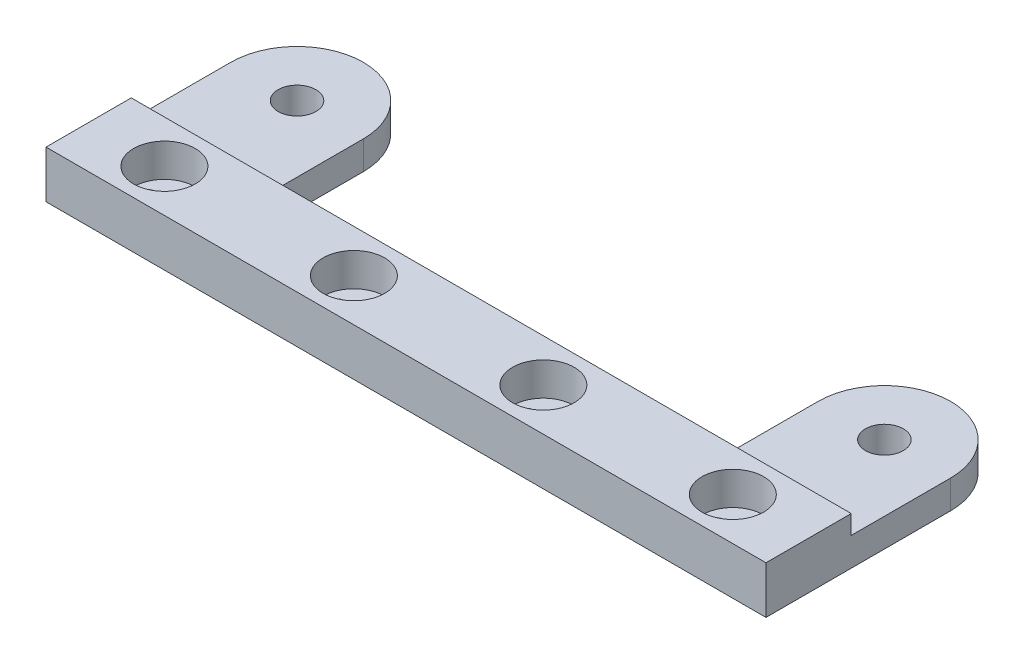
SolidWorks part; units mm, degrees
ref_plane "Front Plane" through (0, 0, 0) normal (0, 0, 1) x (1, 0, 0)
ref_plane "Top Plane" through (0, 0, 0) normal (0, 1, 0) x (1, 0, 0)
ref_plane "Right Plane" through (0, 0, 0) normal (1, 0, 0) x (0, 0, -1)
sketch "Sketch1" plane through (0, 0, 0) normal (0, 1, 0) x (1, 0, 0)
  line L0 (62, 19.5) -> (62, 9)
  line L1 (0, 0) -> (76, 0)
  line L2 (0, 0) -> (0, 9)
  line L3 (0, 9) -> (76, 9)
  line L4 (76, 0) -> (76, 9)
  line L5 (14, 19.5) -> (14, 9)
  line L6 (0, 19.5) -> (0, 9)
  line L7 (76, 9) -> (76, 19.5)
  circle A0 centre (7, 19.5) radius 2
  circle A1 centre (69, 19.5) radius 2
  circle A2 centre (69, 19.5) radius 7
  circle A3 centre (7, 19.5) radius 7
  point P16 (80, 23)
  dimension "D3" = 4
  dimension "D4" = 5
  dimension "D7" = 5
  dimension "D10" = 4
  dimension "D1" = 76
  dimension "D2" = 9
  dimension "D5" = 7
  dimension "D6" = 10.5
  dimension "D8" = 7
  dimension "D9" = 10.5
extrude "Boss-Extrude1" add sketch "Sketch1" along normal blind 3 contours A2 A1 | A2 L3 L7 | A2 L0 L3 | L1 L4 L3 L2 | A3 L3 L5 | A3 A0 | A3 L6 L3
sketch "Sketch2" plane through (0, 3, 0) normal (0, 1, 0) x (1, 0, 0)
  line L0 (76, 0) -> (76, 19.5) construction
  line L1 (0, 0) -> (76, 0)
  line L2 (0, 0) -> (0, 9)
  line L3 (0, 9) -> (76, 9)
  line L4 (76, 0) -> (76, 9)
  dimension "D1" = 9
extrude "Boss-Extrude2" add sketch "Sketch2" along normal blind 2
sketch "Sketch3" plane through (0, 5, 0) normal (0, 1, 0) x (1, 0, 0)
  line L0 (14, 9) -> (0, 9) construction
  line L1 (0, 9) -> (0, 0) construction
  circle A0 centre (8, 4.5) radius 3.25
  circle A1 centre (28, 4.5) radius 3.25
  circle A2 centre (48, 4.5) radius 3.25
  circle A3 centre (68, 4.5) radius 3.25
  circle A8 centre (88, 4.5) radius 3.25 [skipped]
  circle A9 centre (108, 4.5) radius 3.25 [skipped]
  circle A10 centre (128, 4.5) radius 3.25 [skipped]
  circle A11 centre (148, 4.5) radius 3.25 [skipped]
  dimension "D1" = 6.5
  dimension "D2" = 4.5
  dimension "D3" = 8
  dimension "D4" = 8
extrude "Cut-Extrude1" cut sketch "Sketch3" against normal offset from surface (3.5 mm away) 1.5 up to face at (38, 0, -13.75)
sketch "Sketch4" plane through (0, 1.5, 0) normal (0, 1, 0) x (1, 0, 0)
  line L0 (4.75, 4.5) -> (11.25, 4.5) construction
  line L1 (6.25, 4.5) -> (9.75, 4.5) construction
  line L2 (6.25, 5.2) -> (9.75, 5.2)
  line L3 (6.25, 3.8) -> (9.75, 3.8)
  line L4 (26.25, 4.5) -> (29.75, 4.5) construction
  line L5 (26.25, 5.2) -> (29.75, 5.2)
  line L6 (26.25, 3.8) -> (29.75, 3.8)
  line L7 (46.25, 4.5) -> (49.75, 4.5) construction
  line L8 (46.25, 5.2) -> (49.75, 5.2)
  line L9 (46.25, 3.8) -> (49.75, 3.8)
  line L10 (66.25, 4.5) -> (69.75, 4.5) construction
  line L11 (66.25, 5.2) -> (69.75, 5.2)
  line L12 (66.25, 3.8) -> (69.75, 3.8)
  line L178 (106.25, 4.5) -> (109.75, 4.5) construction
  line L179 (106.25, 5.2) -> (109.75, 5.2)
  line L180 (106.25, 3.8) -> (109.75, 3.8)
  line L181 (126.25, 4.5) -> (129.75, 4.5) construction
  line L182 (126.25, 5.2) -> (129.75, 5.2)
  line L183 (126.25, 3.8) -> (129.75, 3.8)
  line L184 (146.25, 4.5) -> (149.75, 4.5) construction
  line L185 (146.25, 5.2) -> (149.75, 5.2)
  line L186 (146.25, 3.8) -> (149.75, 3.8)
  line L187 (86.25, 4.5) -> (89.75, 4.5) construction
  line L188 (86.25, 5.2) -> (89.75, 5.2)
  line L189 (86.25, 3.8) -> (89.75, 3.8)
  line L190 (106.25, 4.5) -> (109.75, 4.5) construction
  line L191 (106.25, 5.2) -> (109.75, 5.2)
  line L192 (106.25, 3.8) -> (109.75, 3.8)
  line L193 (126.25, 4.5) -> (129.75, 4.5) construction
  line L194 (126.25, 5.2) -> (129.75, 5.2)
  line L195 (126.25, 3.8) -> (129.75, 3.8)
  line L196 (146.25, 4.5) -> (149.75, 4.5) construction
  line L197 (146.25, 5.2) -> (149.75, 5.2)
  line L198 (146.25, 3.8) -> (149.75, 3.8)
  line L199 (86.25, 4.5) -> (89.75, 4.5) construction
  line L200 (86.25, 5.2) -> (89.75, 5.2)
  line L201 (86.25, 3.8) -> (89.75, 3.8)
  circle A0 centre (8, 4.5) radius 3.25 construction
  circle A1 centre (8, 4.5) radius 3.25 construction
  arc A2 (6.25, 5.2) -> (6.25, 3.8) centre (6.25, 4.5) ccw
  arc A3 (9.75, 3.8) -> (9.75, 5.2) centre (9.75, 4.5) ccw
  arc A4 (26.25, 5.2) -> (26.25, 3.8) centre (26.25, 4.5) ccw
  arc A5 (29.75, 3.8) -> (29.75, 5.2) centre (29.75, 4.5) ccw
  arc A6 (46.25, 5.2) -> (46.25, 3.8) centre (46.25, 4.5) ccw
  arc A7 (49.75, 3.8) -> (49.75, 5.2) centre (49.75, 4.5) ccw
  arc A8 (66.25, 5.2) -> (66.25, 3.8) centre (66.25, 4.5) ccw
  arc A9 (69.75, 3.8) -> (69.75, 5.2) centre (69.75, 4.5) ccw
  arc A130 (106.25, 5.2) -> (106.25, 3.8) centre (106.25, 4.5) ccw
  arc A131 (109.75, 3.8) -> (109.75, 5.2) centre (109.75, 4.5) ccw
  arc A132 (126.25, 5.2) -> (126.25, 3.8) centre (126.25, 4.5) ccw
  arc A133 (129.75, 3.8) -> (129.75, 5.2) centre (129.75, 4.5) ccw
  arc A134 (146.25, 5.2) -> (146.25, 3.8) centre (146.25, 4.5) ccw
  arc A135 (149.75, 3.8) -> (149.75, 5.2) centre (149.75, 4.5) ccw
  arc A136 (86.25, 5.2) -> (86.25, 3.8) centre (86.25, 4.5) ccw
  arc A137 (89.75, 3.8) -> (89.75, 5.2) centre (89.75, 4.5) ccw
  point P8 (8, 4.5)
  point P14 (8, 4.5)
  point P17 (28, 4.5)
  point P24 (48, 4.5)
  point P31 (68, 4.5)
  point P38 (110, 4.5)
  point P45 (130, 4.5)
  point P52 (150, 4.5)
  point P65 (90, 4.5)
  point P72 (110, 4.5)
  point P79 (130, 4.5)
  point P86 (150, 4.5)
  point P93 (90, 4.5)
  point P100 (110, 4.5)
  point P107 (130, 4.5)
  point P114 (150, 4.5)
  point P121 (90, 4.5)
  point P128 (110, 4.5)
  point P135 (130, 4.5)
  point P142 (150, 4.5)
  point P149 (90, 4.5)
  point P156 (110, 4.5)
  point P163 (130, 4.5)
  point P170 (150, 4.5)
  point P177 (90, 4.5)
  point P184 (110, 4.5)
  point P191 (130, 4.5)
  point P198 (150, 4.5)
  point P205 (90, 4.5)
  point P212 (110, 4.5)
  point P219 (130, 4.5)
  point P226 (150, 4.5)
  point P233 (90, 4.5)
  point P240 (110, 4.5)
  point P247 (130, 4.5)
  point P254 (150, 4.5)
  point P261 (90, 4.5)
  point P268 (110, 4.5)
  point P275 (130, 4.5)
  point P282 (150, 4.5)
  point P289 (90, 4.5)
  point P296 (110, 4.5)
  point P303 (130, 4.5)
  point P310 (150, 4.5)
  point P317 (90, 4.5)
  point P324 (110, 4.5)
  point P331 (130, 4.5)
  point P338 (150, 4.5)
  point P345 (90, 4.5)
  point P352 (110, 4.5)
  point P359 (130, 4.5)
  point P366 (150, 4.5)
  point P373 (90, 4.5)
  point P380 (108, 4.5)
  point P387 (128, 4.5)
  point P394 (148, 4.5)
  point P401 (88, 4.5)
  point P408 (108, 4.5)
  point P415 (128, 4.5)
  point P422 (148, 4.5)
  point P429 (88, 4.5)
  point P436 (108, 4.5)
  point P443 (128, 4.5)
  point P450 (148, 4.5)
  point P457 (88, 4.5)
  dimension "D1" = 3.5
  dimension "D2" = 0.7
  dimension "D3" = 8
extrude "Cut-Extrude2" cut sketch "Sketch4" against normal up to next
